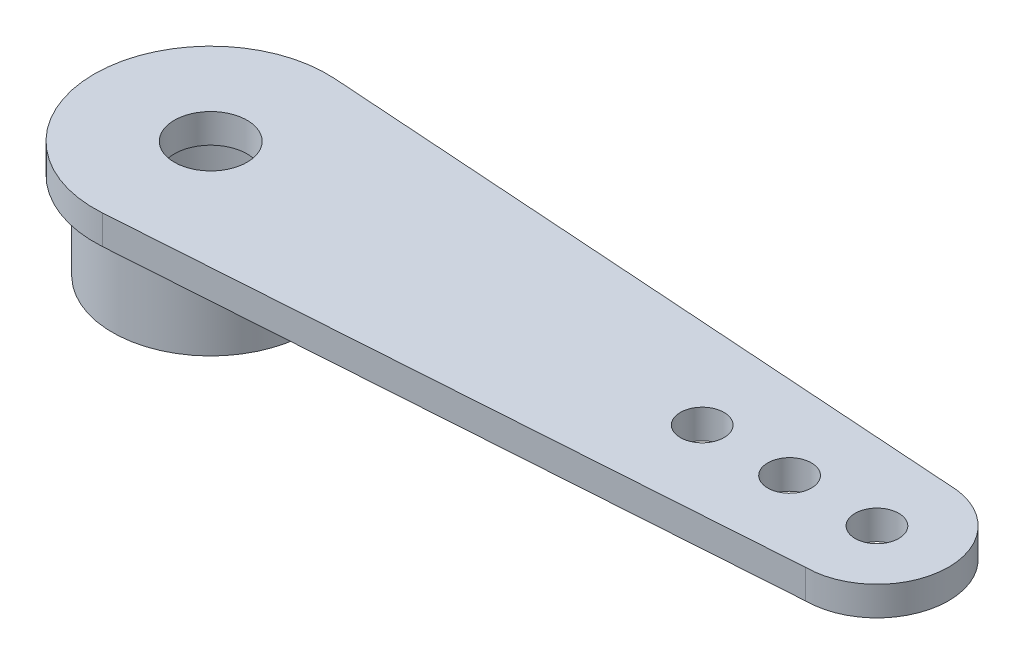
SolidWorks part; units mm, degrees
ref_plane "Front Plane" through (0, 0, 0) normal (0, 0, 1) x (1, 0, 0)
ref_plane "Top Plane" through (0, 0, 0) normal (0, 1, 0) x (1, 0, 0)
ref_plane "Right Plane" through (0, 0, 0) normal (1, 0, 0) x (0, 0, -1)
sketch "Sketch5" plane through (0, 0, 0) normal (0, 1, 0) x (1, 0, 0)
  circle A0 centre (0, 0) radius 2.794
  circle A1 centre (0, 0) radius 3.429
  dimension "D1" = 5.588
  dimension "D2" = 6.858
extrude "Boss-Extrude3" add sketch "Sketch5" along normal blind 3.048
sketch "Sketch6" plane through (0, 3.048, 0) normal (0, 1, 0) x (1, 0, 0)
  line L0 (0, 0) -> (23.241, 0)
  line L1 (23.241, 2.497) -> (0.275, 4.0547)
  line L2 (23.241, -2.497) -> (0.275, -4.0547)
  circle A0 centre (0, 0) radius 1.27
  circle A1 centre (0, 0) radius 4.064
  circle A2 centre (17.145, 0) radius 0.762
  circle A3 centre (20.193, 0) radius 0.762
  circle A4 centre (23.241, 0) radius 0.762
  circle A5 centre (23.241, 0) radius 2.497
  dimension "D1" = 2.54
  dimension "D2" = 1.524
  dimension "D3" = 1.524
  dimension "D4" = 1.524
  dimension "D5" = 8.128
  dimension "D6" = 17.145
  dimension "D7" = 20.193
  dimension "D8" = 23.241
extrude "Boss-Extrude4" add sketch "Sketch6" along normal blind 1.016
